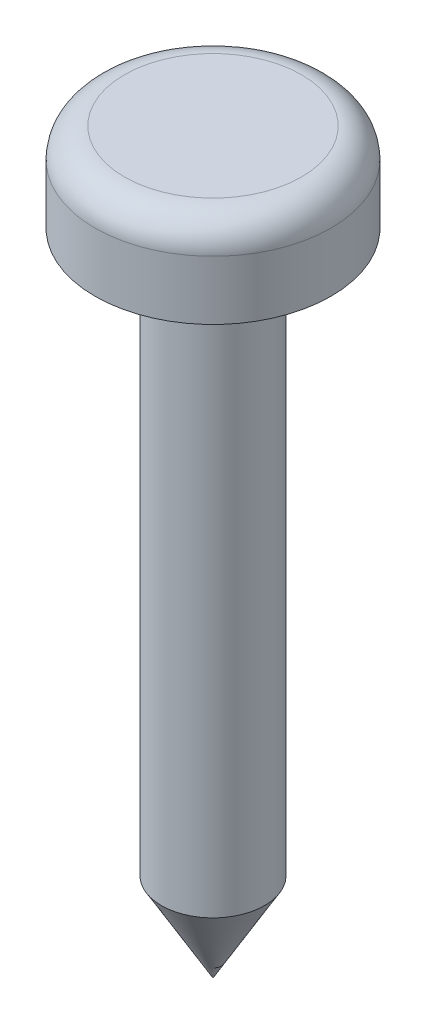
SolidWorks part; units mm, degrees
ref_plane "Front Plane" through (0, 0, 0) normal (0, 0, 1) x (1, 0, 0)
ref_plane "Top Plane" through (0, 0, 0) normal (0, 1, 0) x (1, 0, 0)
ref_plane "Right Plane" through (0, 0, 0) normal (1, 0, 0) x (0, 0, -1)
sketch "Sketch1" plane through (0, 0, 0) normal (0, 0, 1) x (1, 0, 0)
  line L0 (0, 86.3158) -> (0, -82.9612) construction
  line L7 (0, 0) -> (-1.75, 3)
  line L8 (-1.75, 22) -> (-4, 22)
  line L9 (-4, 22) -> (-4, 24)
  line L10 (-3, 25) -> (0, 25)
  line L11 (0, 25) -> (0, 0)
  line L12 (-1.75, 3) -> (-1.75, 22)
  arc A2 (-4, 24) -> (-3, 25) centre (-3, 24) cw
  point P11 (-4, 25)
  dimension "D1" = 3.5
  dimension "D6" = 1
  dimension "D2" = 8
  dimension "D3" = 3
  dimension "D4" = 3
  dimension "D5" = 25
revolve "Revolve2" add sketch "Sketch1" angle 360 about L0
